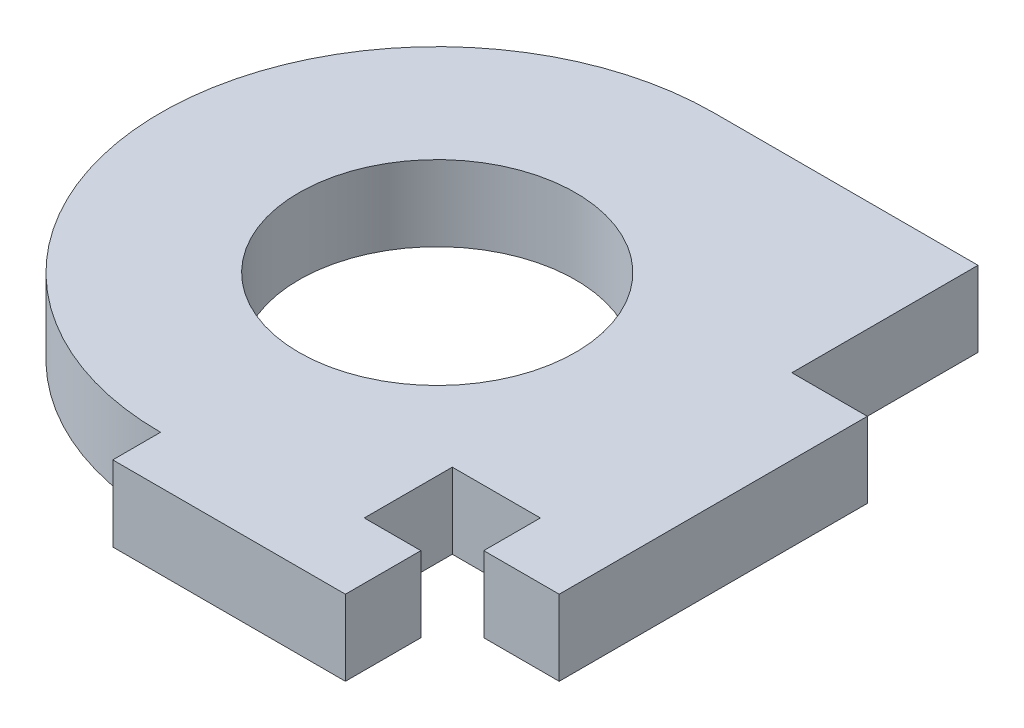
SolidWorks part; units mm, degrees
ref_plane "Front Plane" through (0, 0, 0) normal (0, 0, 1) x (1, 0, 0)
ref_plane "Top Plane" through (0, 0, 0) normal (0, 1, 0) x (1, 0, 0)
ref_plane "Right Plane" through (0, 0, 0) normal (1, 0, 0) x (0, 0, -1)
sketch "Sketch1" plane through (0, 0, 0) normal (0, 1, 0) x (1, 0, 0)
  line L0 (0, 0) -> (0, 7)
  line L5 (-14, -2.2) -> (-14, -6)
  line L7 (-14, -6) -> (4.5, -6)
  line L9 (0, 0) -> (4.5, 0)
  line L12 (4.5, 0) -> (4.5, -6)
  line L13 (0, 7) -> (7, 7)
  line L17 (7, 41.8) -> (7, 27)
  line L28 (7, 27) -> (13, 27)
  line L31 (7, 7) -> (7, 2.5)
  line L32 (7, 2.5) -> (13, 2.5)
  line L34 (13, 2.5) -> (13, 27)
  line L35 (-14, 41.8) -> (7, 41.8)
  arc A0 (-14, 41.8) -> (-14, -2.2) centre (-14, 19.8) ccw
  circle A1 centre (-14, 19.8) radius 11
  dimension "D3" = 22
  dimension "D4" = 22
  dimension "D10" = 6
  dimension "D1" = 19.8
  dimension "D2" = 21
  dimension "D5" = 6
  dimension "D6" = 18.5
  dimension "D7" = 7
  dimension "D8" = 7
  dimension "D9" = 4.5
  dimension "D11" = 4.5
  dimension "D12" = 20
extrude "Boss-Extrude1" add sketch "Sketch1" along normal blind 6
